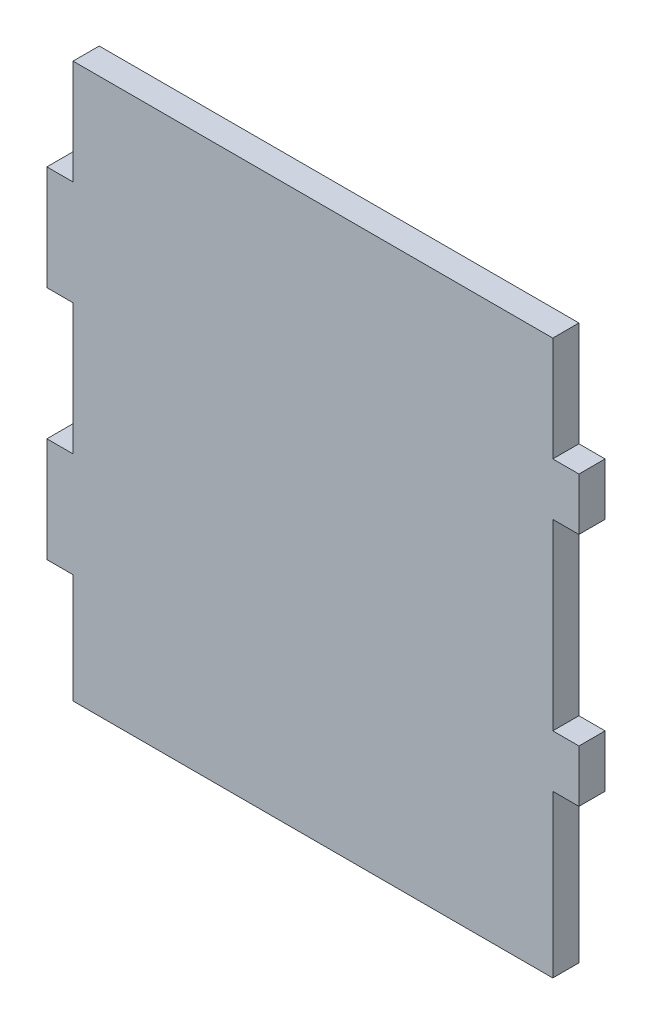
SolidWorks part; units mm, degrees
ref_plane "Přední rovina" through (0, 0, 0) normal (0, 0, 1) x (1, 0, 0)
ref_plane "Horní rovina" through (0, 0, 0) normal (0, 1, 0) x (1, 0, 0)
ref_plane "Pravá rovina" through (0, 0, 0) normal (1, 0, 0) x (0, 0, -1)
sketch "Skica1" plane through (0, 0, 0) normal (0, 0, 1) x (1, 0, 0)
  line L12 (0, 0) -> (55, 0)
  line L13 (0, 0) -> (0, -12)
  line L14 (55, 0) -> (55, -12)
  line L15 (0, -63.54) -> (55, -63.54)
  line L17 (0, -12) -> (-3, -12)
  line L18 (0, -24) -> (-3, -24)
  line L19 (-3, -12) -> (-3, -24)
  line L20 (0, -39) -> (-3, -39)
  line L21 (0, -51) -> (-3, -51)
  line L22 (-3, -39) -> (-3, -51)
  line L23 (55, -45) -> (58, -45)
  line L24 (58, -39) -> (58, -45)
  line L25 (55, -39) -> (58, -39)
  line L26 (55, -12) -> (58, -12)
  line L27 (55, -18) -> (58, -18)
  line L28 (58, -12) -> (58, -18)
  line L29 (55, -45) -> (55, -63.54)
  line L30 (55, -18) -> (55, -39)
  line L31 (0, -24) -> (0, -39)
  line L32 (0, -51) -> (0, -63.54)
  dimension "D1" = 55
  dimension "D2" = 63.54
  dimension "D3" = 3
  dimension "D4" = 3
  dimension "D5" = 12
  dimension "D6" = 12
  dimension "D7" = 12
  dimension "D8" = 15
  dimension "D9" = 6
  dimension "D10" = 6
  dimension "D11" = 12
  dimension "D12" = 21
  dimension "D13" = 3
  dimension "D14" = 3
extrude "Přidat vysunutím1" add sketch "Skica1" along normal blind 3
